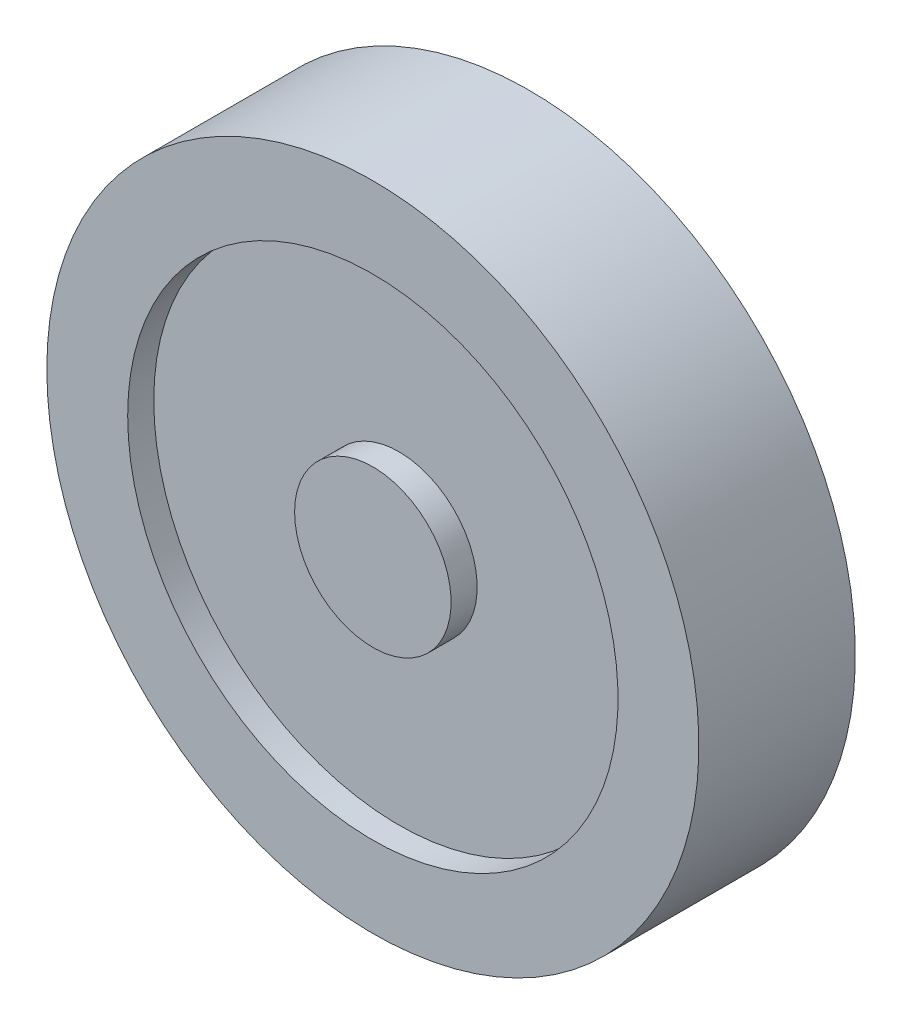
SolidWorks part; units mm, degrees
ref_plane "Front Plane" through (0, 0, 0) normal (0, 0, 1) x (1, 0, 0)
ref_plane "Top Plane" through (0, 0, 0) normal (0, 1, 0) x (1, 0, 0)
ref_plane "Right Plane" through (0, 0, 0) normal (1, 0, 0) x (0, 0, -1)
ref_plane "PL_Y_62p50" through (0, 62.5, 0) normal (0, 1, 0) x (1, 0, 0)
sketch "SK_P01_Wheel125x30" plane through (0, 62.5, 0) normal (0, 1, 0) x (1, 0, 0)
  line L0 (0, 15) -> (15, 15)
  line L1 (15, 15) -> (15, 10)
  line L2 (15, 10) -> (47, 10)
  line L3 (47, 10) -> (47, 15)
  line L4 (47, 15) -> (62.5, 15)
  line L5 (62.5, 15) -> (62.5, -15)
  line L6 (62.5, -15) -> (47, -15)
  line L7 (47, -15) -> (47, -10)
  line L8 (47, -10) -> (15, -10)
  line L9 (15, -10) -> (15, -15)
  line L10 (15, -15) -> (0, -15)
  line L11 (0, -15) -> (0, 15)
  line L12 (0, 20) -> (0, -20) construction
revolve "P01_Wheel125x30" add sketch "SK_P01_Wheel125x30" angle 360 about L12
